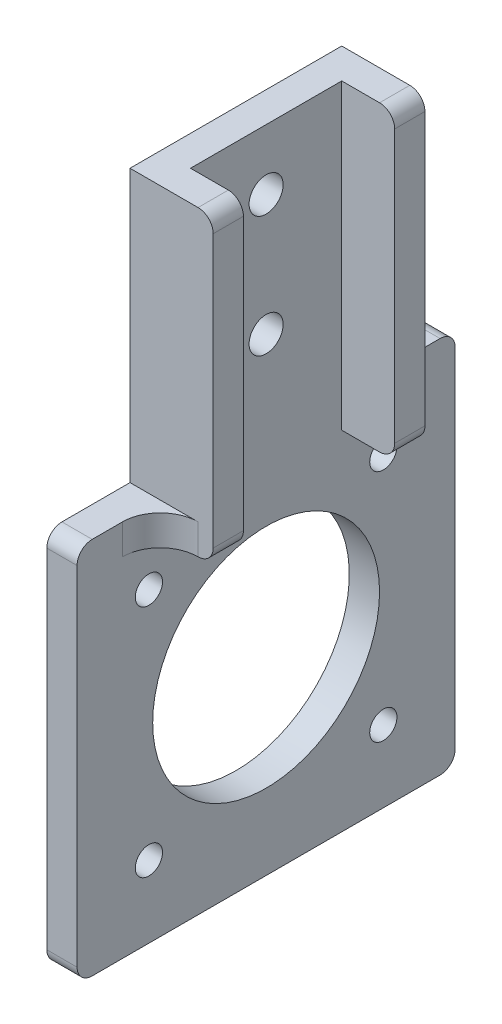
SolidWorks part; units mm, degrees
ref_plane "Front Plane" through (0, 0, 0) normal (0, 0, 1) x (1, 0, 0)
ref_plane "Top Plane" through (0, 0, 0) normal (0, 1, 0) x (1, 0, 0)
ref_plane "Right Plane" through (0, 0, 0) normal (1, 0, 0) x (0, 0, -1)
sketch "Sketch1" plane through (0, 0, 0) normal (0, 1, 0) x (1, 0, 0)
  line L1 (-10, -10) -> (10, -10)
  line L2 (-10, -10) -> (-10, 10)
  line L3 (-10, 10) -> (10, 10)
  line L4 (10, -10) -> (10, 10)
  line L5 (-10, -10) -> (10, 10) construction
  line L6 (-10, 10) -> (10, -10) construction
  line L7 (-14, 14) -> (14, 14)
  line L8 (-14, 14) -> (-14, -14)
  line L9 (-14, -14) -> (14, -14)
  line L10 (14, 14) -> (14, -14)
  line L11 (-14, 14) -> (14, -14) construction
  line L12 (-14, -14) -> (14, 14) construction
  point P0 (0, 0)
  point P5 (0, 0)
  dimension "D1" = 20
  dimension "D2" = 28
extrude "Boss-Extrude1" add sketch "Sketch1" along normal blind 40
sketch "Sketch2" plane through (-14, 0, 0) normal (-1, 0, 0) x (0, 0, 1)
  line L0 (0, 40) -> (0, 32)
  line L1 (0, 0) -> (0, 16)
  line L4 (-14, 0) -> (14, 0)
  line L5 (14, 0) -> (14, 40)
  line L6 (14, 40) -> (-14, 40)
  line L7 (-14, 40) -> (-14, 0)
  line L8 (-14, 0) -> (14, 0)
  line L9 (14, 0) -> (14, 40)
  line L10 (14, 40) -> (-14, 40)
  line L11 (-14, 40) -> (-14, 0)
  circle A0 centre (0, 32) radius 2.25
  circle A1 centre (0, 16) radius 2.25
  dimension "D3" = 4.5
  dimension "D5" = 4.5
  dimension "D2" = 8
  dimension "D4" = 16
  dimension "D1" = 0
extrude "Cut-Extrude1" cut sketch "Sketch2" against normal blind 30
sketch "Sketch5" plane through (-14, 0, 0) normal (-1, 0, 0) x (0, 0, 1)
  line L0 (0, 0) -> (0, -21)
  line L1 (0, -21) -> (-15.4998, -5.5002) construction
  line L2 (-25, -46) -> (25, -46)
  line L3 (-25, -46) -> (-25, 4)
  line L4 (-14, 0) -> (14, 0)
  line L5 (14, 0) -> (14, 40)
  line L6 (14, 40) -> (-14, 40)
  line L7 (-14, 40) -> (-14, 0)
  line L8 (-14, 0) -> (14, 0)
  line L9 (14, 0) -> (14, 40)
  line L10 (14, 40) -> (-14, 40)
  line L11 (-14, 40) -> (-14, 0)
  line L12 (-25, 4) -> (25, 4)
  line L13 (25, -46) -> (25, 4)
  line L14 (-25, -46) -> (25, 4) construction
  line L15 (-25, 4) -> (25, -46) construction
  line L16 (-15.4998, -5.5002) -> (15.4998, -5.5002) construction
  line L17 (15.4998, -5.5002) -> (15.4998, -36.4998) construction
  line L18 (15.4998, -36.4998) -> (-15.4998, -36.4998) construction
  circle A0 centre (-15.4998, -5.5002) radius 1.8
  circle A1 centre (15.4998, -5.5002) radius 1.8
  circle A2 centre (15.4998, -36.4998) radius 1.8
  circle A3 centre (-15.4998, -36.4998) radius 1.8
  circle A4 centre (0, -21) radius 15
  dimension "D5" = 3.6
  dimension "D6" = 30
  dimension "D2" = 21
  dimension "D3" = 50
  dimension "D4" = 21.92
  dimension "D1" = 0
extrude "Boss-Extrude2" add sketch "Sketch5" against normal up to surface (4 mm away) up to face at (-10, 16, -2.25)
sketch "Sketch6" plane through (0, 0, 0) normal (0, -1, 0) x (1, 0, 0)
  line L0 (-10, 14) -> (14, 14) construction
  line L1 (-3, 14) -> (14, 14)
  line L2 (-3, 14) -> (-3, -14)
  line L3 (-3, -14) -> (14, -14)
  line L4 (14, 14) -> (14, -14)
  dimension "D1" = 17
extrude "Cut-Extrude2" cut sketch "Sketch6" against normal blind 40
fillet "Fillet1" radius 2 8 edges at (-3, 0, -12) (-3, 0, 12) (-3, 40, -12) (-3, 40, 12) (-12, 4, 25) (-12, 4, -25) (-12, -46, -25) (-12, -46, 25)
fillet "Fillet2" radius 5 2 edges at (-10, 2, -14) (-10, 2, 14)
